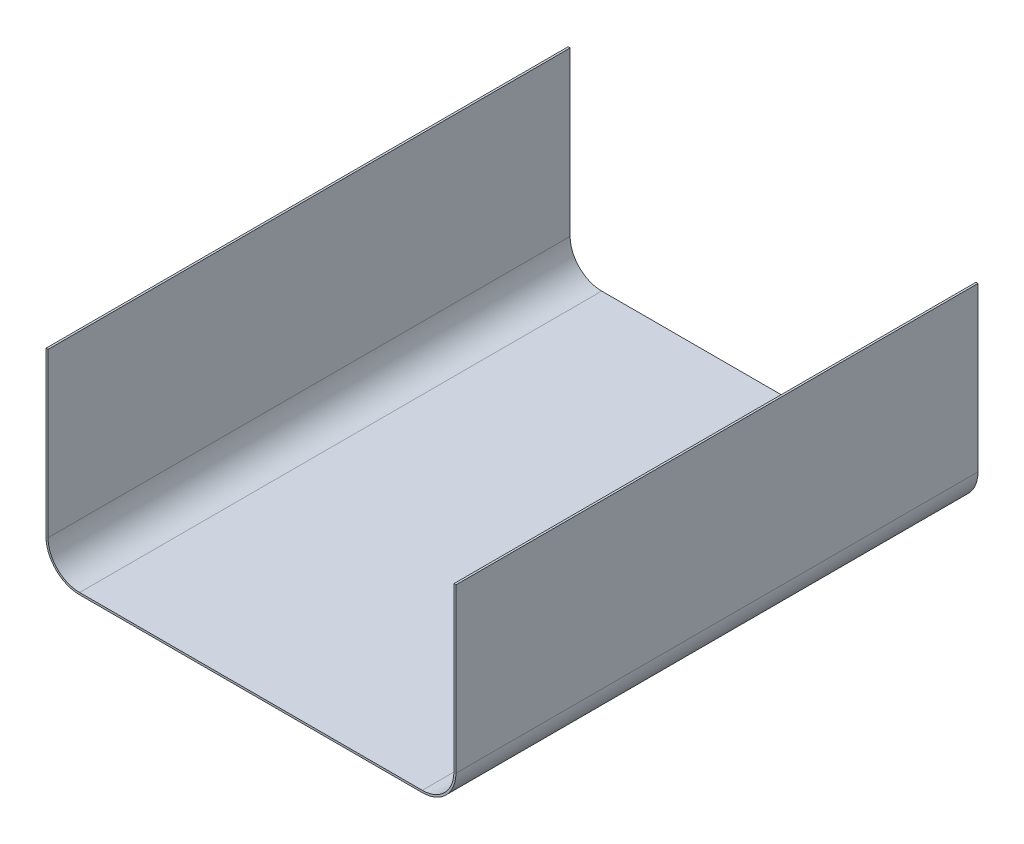
SolidWorks part; units mm, degrees
ref_plane "Front Plane" through (0, 0, 0) normal (0, 0, 1) x (1, 0, 0)
ref_plane "Top Plane" through (0, 0, 0) normal (0, 1, 0) x (1, 0, 0)
ref_plane "Right Plane" through (0, 0, 0) normal (1, 0, 0) x (0, 0, -1)
sketch "Sketch1" plane through (0, 0, 0) normal (0, 0, 1) x (1, 0, 0)
  line L0 (0, 0) -> (0, -127)
  line L1 (25.4, -152.4) -> (292.1, -152.4)
  line L2 (317.5, -127) -> (317.5, 0)
  line L3 (-0.7937, 0) -> (-0.7937, -127)
  line L4 (25.4, -153.1938) -> (292.1, -153.1938)
  line L5 (318.2937, -127) -> (318.2937, 0)
  line L6 (0.7937, 0) -> (0.7937, -127)
  line L7 (25.4, -151.6062) -> (292.1, -151.6062)
  line L8 (316.7063, -127) -> (316.7063, 0)
  line L9 (-0.7937, 0) -> (0.7937, 0)
  line L10 (316.7063, 0) -> (318.2937, 0)
  arc A0 (292.1, -152.4) -> (317.5, -127) centre (292.1, -127) ccw
  arc A1 (25.4, -152.4) -> (0, -127) centre (25.4, -127) cw
  arc A2 (25.4, -153.1938) -> (-0.7937, -127) centre (25.4, -127) cw
  arc A3 (292.1, -153.1938) -> (318.2937, -127) centre (292.1, -127) ccw
  arc A4 (25.4, -151.6062) -> (0.7937, -127) centre (25.4, -127) cw
  arc A5 (292.1, -151.6062) -> (316.7063, -127) centre (292.1, -127) ccw
  point P7 (317.5, -152.4)
  point P10 (0, -152.4)
  dimension "D3" = 25.4
  dimension "D1" = 152.4
  dimension "D2" = 317.5
  dimension "D4" = 0.7937
  dimension "D5" = 0.7937
extrude "Boss-Extrude1" add sketch "Sketch1" along normal blind 406.4 contours A5 L7 A4 L6 L9 L0 A1 L1 A0 L2 L10 L8 | L4 A3 L5 L10 L2 A0 L1 A1 L0 L9 L3 A2
